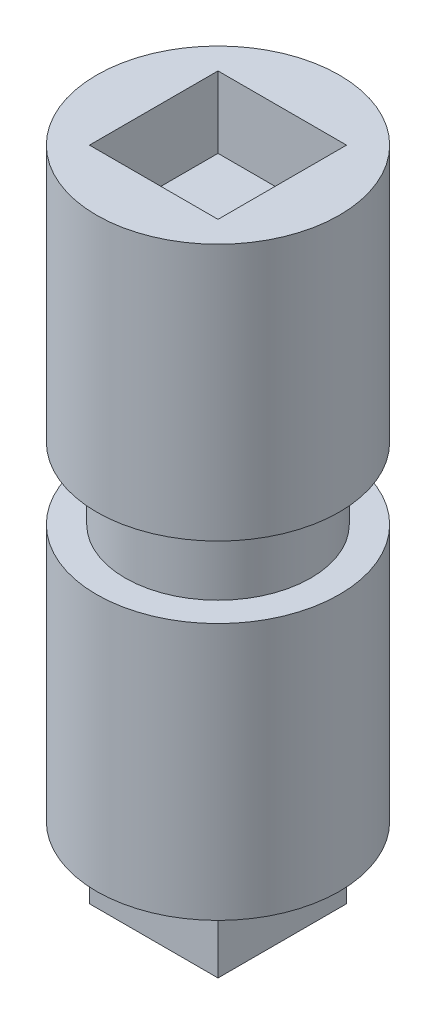
SolidWorks part; units mm, degrees
ref_plane "Front Plane" through (0, 0, 0) normal (0, 0, 1) x (1, 0, 0)
ref_plane "Top Plane" through (0, 0, 0) normal (0, 1, 0) x (1, 0, 0)
ref_plane "Right Plane" through (0, 0, 0) normal (1, 0, 0) x (0, 0, -1)
sketch "Sketch1" plane through (0, 0, 0) normal (0, 1, 0) x (1, 0, 0)
  circle A0 centre (0, 0) radius 85
extrude "Boss-Extrude2" add sketch "Sketch1" along normal blind 180
sketch "Sketch2" plane through (0, 0, 0) normal (0, -1, 0) x (1, 0, 0)
  line L1 (45, 45) -> (-45, 45)
  line L2 (45, 45) -> (45, -45)
  line L3 (45, -45) -> (-45, -45)
  line L4 (-45, 45) -> (-45, -45)
  line L5 (45, 45) -> (-45, -45) construction
  line L6 (45, -45) -> (-45, 45) construction
  point P0 (0, 0)
extrude "Boss-Extrude3" add sketch "Sketch2" along normal blind 50
sketch "Sketch3" plane through (0, 180, 0) normal (0, 1, 0) x (1, 0, 0)
  point P0 (0, 0)
sketch "Sketch4" plane through (0, 180, 0) normal (0, 1, 0) x (1, 0, 0)
  circle A0 centre (0, 0) radius 65
extrude "Boss-Extrude4" add sketch "Sketch4" along normal blind 50
sketch "Sketch5" plane through (0, 230, 0) normal (0, 1, 0) x (1, 0, 0)
  circle A0 centre (0, 0) radius 85
extrude "Boss-Extrude5" add sketch "Sketch5" along normal blind 180
sketch "Sketch6" plane through (0, 410, 0) normal (0, 1, 0) x (1, 0, 0)
  line L1 (-45, 45) -> (45, 45)
  line L2 (-45, 45) -> (-45, -45)
  line L3 (-45, -45) -> (45, -45)
  line L4 (45, 45) -> (45, -45)
  line L5 (-45, 45) -> (45, -45) construction
  line L6 (-45, -45) -> (45, 45) construction
  point P0 (0, 0)
extrude "Cut-Extrude2" cut sketch "Sketch6" against normal blind 50
